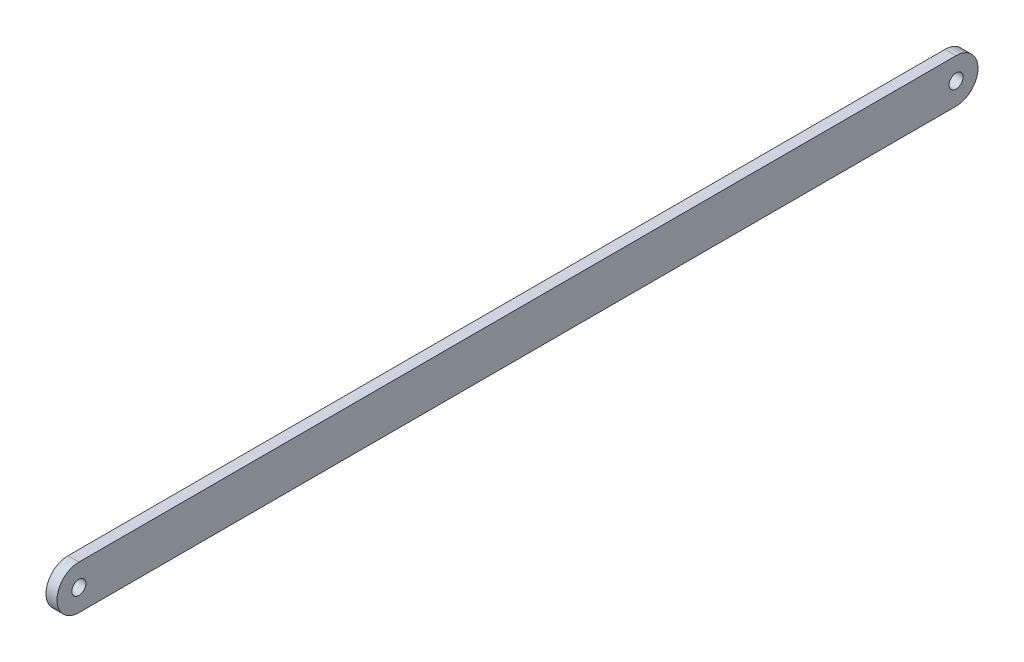
SolidWorks part; units mm, degrees
ref_plane "Front Plane" through (0, 0, 0) normal (0, 0, 1) x (1, 0, 0)
ref_plane "Top Plane" through (0, 0, 0) normal (0, 1, 0) x (1, 0, 0)
ref_plane "Right Plane" through (0, 0, 0) normal (1, 0, 0) x (0, 0, -1)
sketch "Sketch1" plane through (0, 0, 0) normal (1, 0, 0) x (0, 0, -1)
  line L0 (0, 0) -> (-254, 0) construction
  line L1 (0, -6.35) -> (-254, -6.35)
  line L2 (0, 6.35) -> (-254, 6.35)
  arc A0 (0, -6.35) -> (0, 6.35) centre (0, 0) ccw
  arc A1 (-254, 6.35) -> (-254, -6.35) centre (-254, 0) ccw
  circle A2 centre (-254, 0) radius 2.032
  circle A3 centre (0, 0) radius 2.032
  point P3 (-127, 0)
  dimension "D3" = 4.064
  dimension "D1" = 254
  dimension "D2" = 12.7
extrude "Boss-Extrude1" add sketch "Sketch1" along normal blind 3.175
